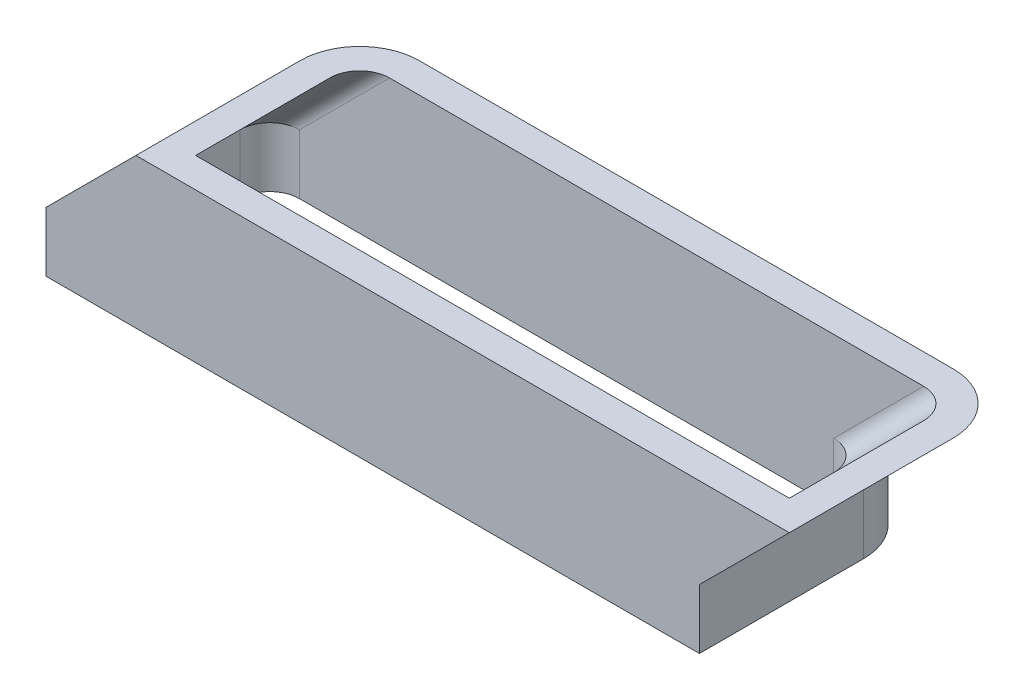
SolidWorks part; units mm, degrees
ref_plane "Спереди" through (0, 0, 0) normal (0, 0, 1) x (1, 0, 0)
ref_plane "Сверху" through (0, 0, 0) normal (0, 1, 0) x (1, 0, 0)
ref_plane "Справа" through (0, 0, 0) normal (1, 0, 0) x (0, 0, -1)
sketch "Эскиз1" plane through (0, 0, 0) normal (0, 1, 0) x (1, 0, 0)
  line L1 (-11.4208, 1.2097) -> (6.4792, 1.2097)
  line L2 (-12.4208, 0.2097) -> (-12.4208, -4.2903)
  line L3 (-12.4208, -4.2903) -> (7.4792, -4.2903)
  line L4 (7.4792, 0.2097) -> (7.4792, -4.2903)
  line L12 (-11.4208, 2.2097) -> (6.4792, 2.2097)
  line L13 (8.4792, 0.2097) -> (8.4792, -5.2903)
  line L14 (-13.4208, -5.2903) -> (8.4792, -5.2903)
  line L15 (-13.4208, 0.2097) -> (-13.4208, -5.2903)
  arc A0 (6.4792, 1.2097) -> (7.4792, 0.2097) centre (6.4792, 0.2097) cw
  arc A1 (-11.4208, 1.2097) -> (-12.4208, 0.2097) centre (-11.4208, 0.2097) ccw
  arc A6 (6.4792, 2.2097) -> (8.4792, 0.2097) centre (6.4792, 0.2097) cw
  arc A7 (-11.4208, 2.2097) -> (-13.4208, 0.2097) centre (-11.4208, 0.2097) ccw
  point P6 (7.4792, 1.2097)
  point P9 (-12.4208, 1.2097)
  dimension "D3" = 5.5
  dimension "D1" = 19.9
  dimension "D2" = 1
sketch "Эскиз2" plane through (0, 0, 0) normal (0, 0, 1) x (1, 0, 0)
  line L0 (-13.4208, 0) -> (-10.407, 3.0137)
  point P6 (0, 0)
sweep "По траектории1" add profiles "Эскиз1" path "Эскиз2"
sketch "Эскиз3" plane through (0, 0, 0) normal (0, -1, 0) x (1, 0, 0)
  line L4 (8.4792, -0.2097) -> (8.4792, 5.2903)
  line L5 (8.4792, 5.2903) -> (-13.4208, 5.2903)
  line L6 (-13.4208, 5.2903) -> (-13.4208, -0.2097)
  line L7 (-11.4208, -2.2097) -> (6.4792, -2.2097)
  line L8 (7.4792, -0.2097) -> (7.4792, 4.2903)
  line L9 (-11.4208, -1.2097) -> (6.4792, -1.2097)
  line L10 (-12.4208, 4.2903) -> (-12.4208, -0.2097)
  line L11 (7.4792, 4.2903) -> (-12.4208, 4.2903)
  line L16 (7.4792, -0.2097) -> (7.4792, 4.2903)
  line L17 (-11.4208, -1.2097) -> (6.4792, -1.2097)
  line L18 (-12.4208, 4.2903) -> (-12.4208, -0.2097)
  line L19 (7.4792, 4.2903) -> (-12.4208, 4.2903)
  arc A2 (-13.4208, -0.2097) -> (-11.4208, -2.2097) centre (-11.4208, -0.2097) ccw
  arc A3 (6.4792, -2.2097) -> (8.4792, -0.2097) centre (6.4792, -0.2097) ccw
  arc A4 (6.4792, -1.2097) -> (7.4792, -0.2097) centre (6.4792, -0.2097) ccw
  arc A5 (-12.4208, -0.2097) -> (-11.4208, -1.2097) centre (-11.4208, -0.2097) ccw
  arc A8 (6.4792, -1.2097) -> (7.4792, -0.2097) centre (6.4792, -0.2097) ccw
  arc A9 (-12.4208, -0.2097) -> (-11.4208, -1.2097) centre (-11.4208, -0.2097) ccw
  point P16 (0, 0)
  dimension "D1" = 0
  dimension "D2" = 1
extrude "Бобышка-Вытянуть2" add sketch "Эскиз3" along normal blind 2
